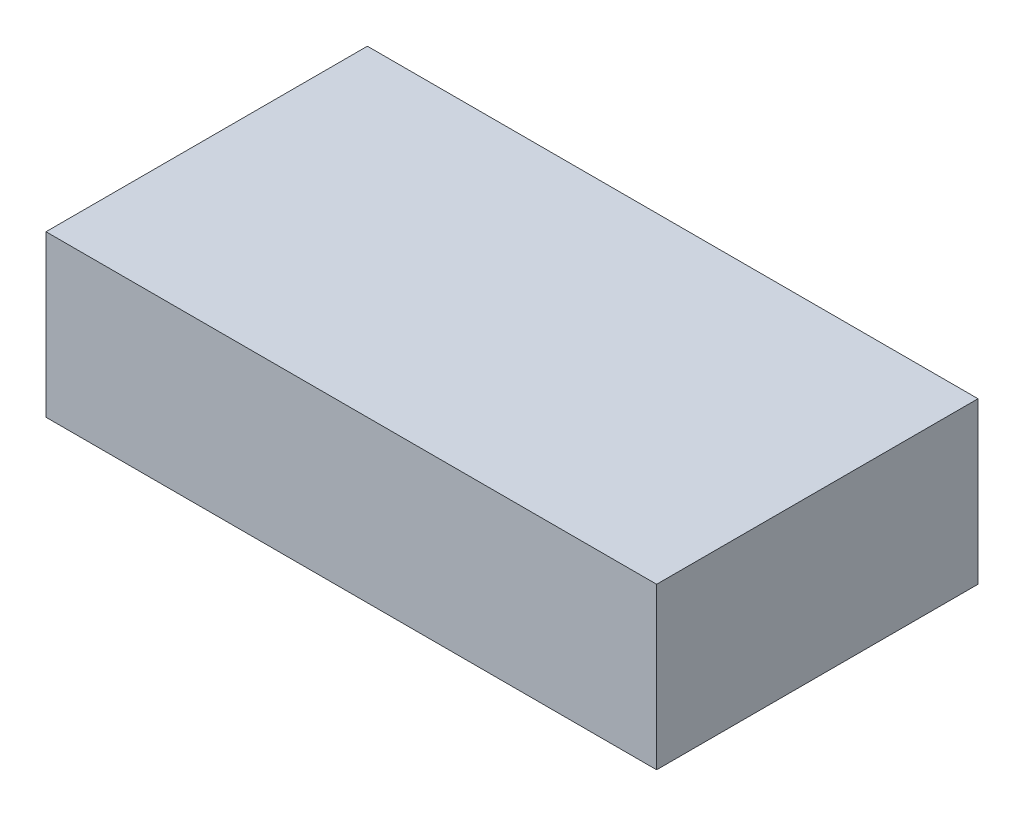
SolidWorks part; units mm, degrees
ref_plane "Front Plane" through (0, 0, 0) normal (0, 0, 1) x (1, 0, 0)
ref_plane "Top Plane" through (0, 0, 0) normal (0, 1, 0) x (1, 0, 0)
ref_plane "Right Plane" through (0, 0, 0) normal (1, 0, 0) x (0, 0, -1)
sketch "Sketch2" plane through (0, 0, 0) normal (0, 1, 0) x (1, 0, 0)
  line L1 (-28.5, -15) -> (28.5, -15)
  line L2 (-28.5, -15) -> (-28.5, 15)
  line L3 (-28.5, 15) -> (28.5, 15)
  line L4 (28.5, -15) -> (28.5, 15)
  line L5 (-28.5, -15) -> (28.5, 15) construction
  line L6 (-28.5, 15) -> (28.5, -15) construction
  point P0 (0, 0)
  dimension "D1" = 57
  dimension "D2" = 30
extrude "Battery" add sketch "Sketch2" along normal blind 15
